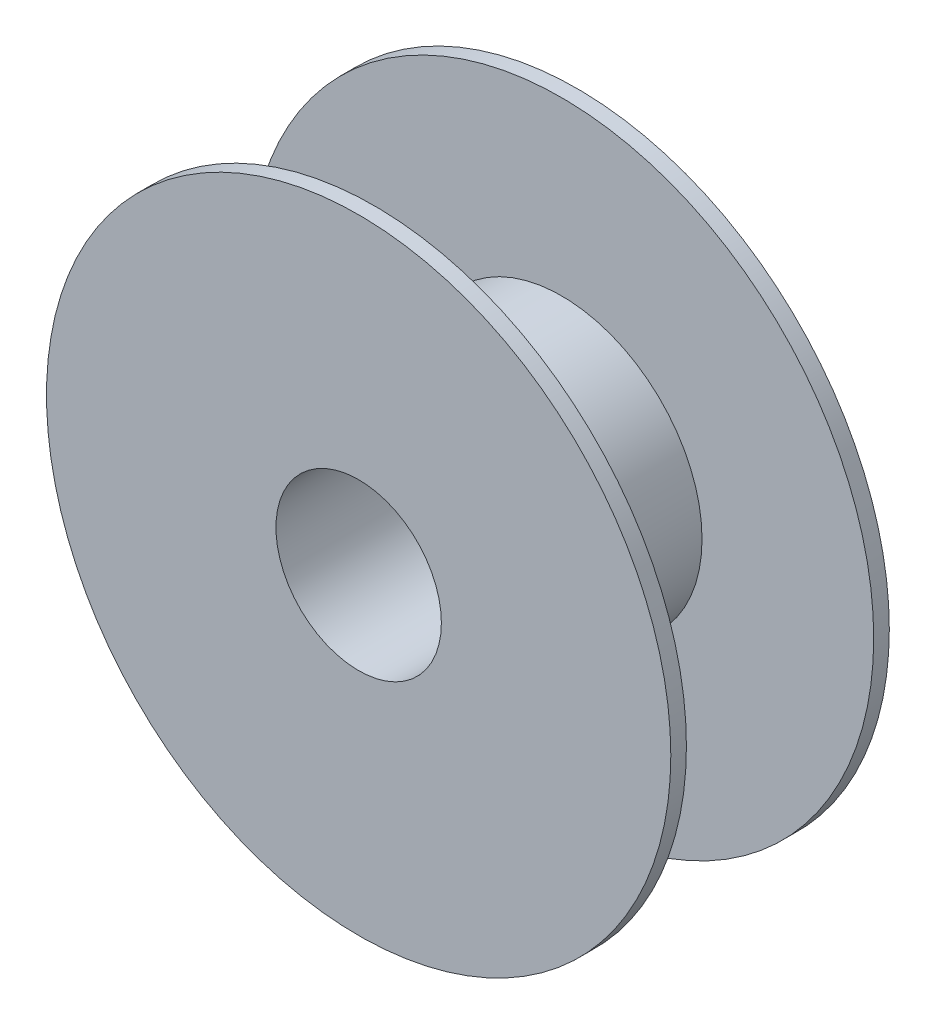
SolidWorks part; units mm, degrees
ref_plane "Front Plane" through (0, 0, 0) normal (0, 0, 1) x (1, 0, 0)
ref_plane "Top Plane" through (0, 0, 0) normal (0, 1, 0) x (1, 0, 0)
ref_plane "Right Plane" through (0, 0, 0) normal (1, 0, 0) x (0, 0, -1)
sketch "Sketch1" plane through (0, 0, 0) normal (0, 0, 1) x (1, 0, 0)
  circle A0 centre (0, 0) radius 100
  circle A1 centre (0, 0) radius 26.5
  dimension "D1" = 200
  dimension "D2" = 53
extrude "Boss-Extrude1" add sketch "Sketch1" along normal blind 70
sketch "Sketch2" plane through (0, 0, 0) normal (0, 1, 0) x (1, 0, 0)
  line L0 (0, 0) -> (0, 50000) construction
  line L1 (100, 0) -> (-100, 0) construction
  line L2 (-100, -5) -> (-45, -5)
  line L3 (-100, -5) -> (-100, -65)
  line L4 (-100, -65) -> (-45, -65)
  line L5 (-45, -5) -> (-45, -65)
  line L6 (-100, -70) -> (100, -70) construction
  line L7 (-100, 0) -> (-100, -70) construction
  dimension "D1" = 5
  dimension "D2" = 5
  dimension "D3" = 55
revolve "Cut-Revolve1" cut sketch "Sketch2" angle 360 about L0
